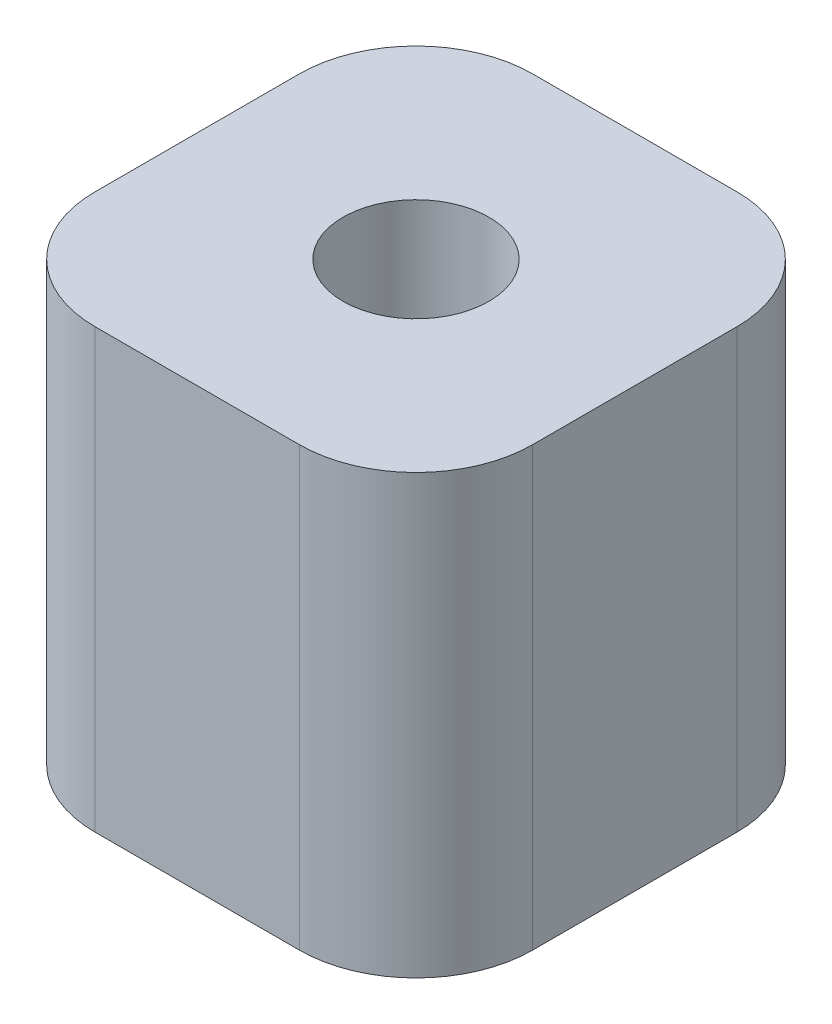
SolidWorks part; units mm, degrees
ref_plane "Front Plane" through (0, 0, 0) normal (0, 0, 1) x (1, 0, 0)
ref_plane "Top Plane" through (0, 0, 0) normal (0, 1, 0) x (1, 0, 0)
ref_plane "Right Plane" through (0, 0, 0) normal (1, 0, 0) x (0, 0, -1)
sketch "Sketch1" plane through (0, 0, 0) normal (0, 1, 0) x (1, 0, 0)
  line L0 (0, 3.75) -> (0, 0) construction
  line L1 (-1.75, 3.75) -> (1.75, 3.75)
  line L2 (-3.75, 1.75) -> (-3.75, -1.75)
  line L3 (-1.75, -3.75) -> (1.75, -3.75)
  line L4 (3.75, 1.75) -> (3.75, -1.75)
  line L5 (0, 0) -> (-3.75, 0) construction
  arc A0 (1.75, 3.75) -> (3.75, 1.75) centre (1.75, 1.75) cw
  arc A1 (-3.75, -1.75) -> (-1.75, -3.75) centre (-1.75, -1.75) ccw
  arc A2 (1.75, -3.75) -> (3.75, -1.75) centre (1.75, -1.75) ccw
  arc A3 (-1.75, 3.75) -> (-3.75, 1.75) centre (-1.75, 1.75) ccw
  point P10 (3.75, 3.75)
  point P17 (-3.75, 3.75)
  dimension "D2" = 2
  dimension "D1" = 7.5
extrude "Boss-Extrude1" add sketch "Sketch1" along normal blind 7.5
sketch "Sketch2" plane through (0, 7.5, 0) normal (0, 1, 0) x (1, 0, 0)
  circle A0 centre (0, 0) radius 1.25
  dimension "D1" = 2.5
extrude "Cut-Extrude1" cut sketch "Sketch2" against normal blind 2.5
